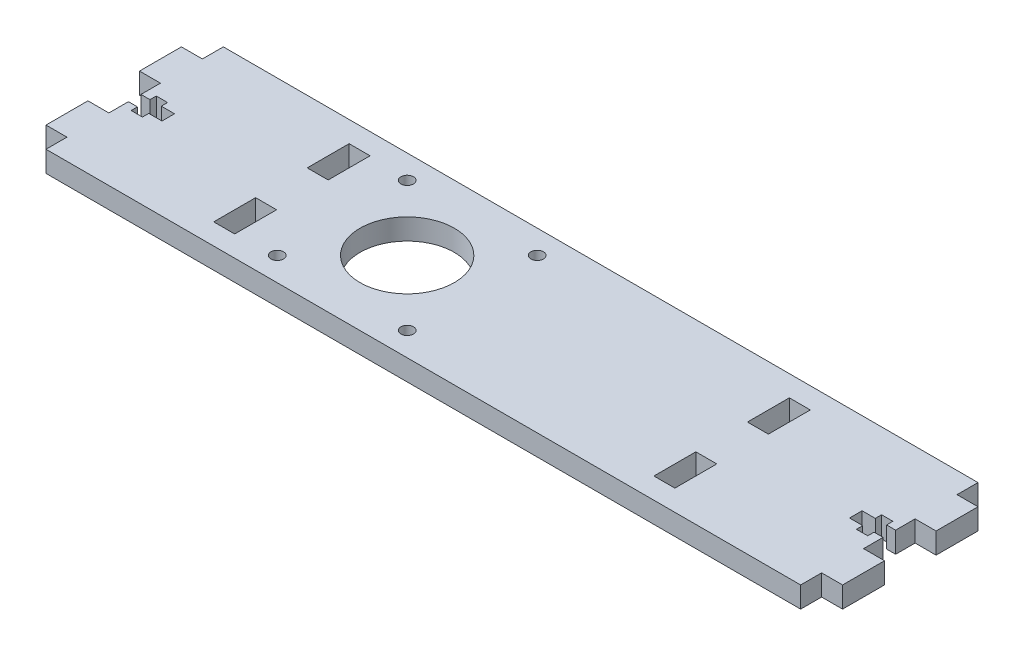
SolidWorks part; units mm, degrees
ref_plane "前视基准面" through (0, 0, 0) normal (0, 0, 1) x (1, 0, 0)
ref_plane "上视基准面" through (0, 0, 0) normal (0, 1, 0) x (1, 0, 0)
ref_plane "右视基准面" through (0, 0, 0) normal (1, 0, 0) x (0, 0, -1)
sketch "草图1" plane through (0, 0, 0) normal (0, 1, 0) x (1, 0, 0)
  line L0 (-5, 66.5434) -> (-5, -19.0663) construction
  line L1 (0, 0) -> (180, 0)
  line L2 (0, 0) -> (0, 5)
  line L3 (0, 42.3) -> (81, 42.3)
  line L4 (180, 0) -> (180, 5)
  line L5 (35, 79.204) -> (35, -20.674) construction
  line L6 (140, 82.0175) -> (140, -23.8894) construction
  line L7 (40, 79.204) -> (40, -15.449) construction
  line L8 (145, 75.274) -> (145, -20.674) construction
  line L9 (-24.6648, 21.15) -> (199.6086, 21.15) construction
  line L10 (90, 93.9854) -> (90, -20.674) construction
  line L11 (65, 59.3981) -> (65, -15.449) construction
  line L12 (0, 37.3) -> (0, 42.3)
  line L13 (0, 37.3) -> (-5, 37.3)
  line L14 (0, 15) -> (0, 19.659)
  line L15 (0, 27.3) -> (-5, 27.3)
  line L16 (-5, 37.3) -> (-5, 27.3)
  line L17 (0, 15) -> (-5, 15)
  line L18 (180, 37.3) -> (180, 42.3)
  line L19 (0, 5) -> (-5, 5)
  line L20 (-5, 15) -> (-5, 5)
  line L21 (180, 37.3) -> (185, 37.3)
  line L22 (180, 15) -> (180, 19.659)
  line L23 (180, 27.3) -> (185, 27.3)
  line L24 (185, 37.3) -> (185, 27.3)
  line L25 (180, 15) -> (185, 15)
  line L26 (99, 42.3) -> (180, 42.3)
  line L27 (180, 5) -> (185, 5)
  line L28 (185, 15) -> (185, 5)
  line L29 (49.5, 36.65) -> (80.5, 36.65) construction
  line L30 (49.5, 36.65) -> (49.5, 5.65) construction
  line L31 (49.5, 5.65) -> (80.5, 5.65) construction
  line L32 (80.5, 36.65) -> (80.5, 5.65) construction
  line L33 (49.5, 36.65) -> (80.5, 5.65) construction
  line L34 (49.5, 5.65) -> (80.5, 36.65) construction
  line L35 (35, 37.3) -> (40, 37.3)
  line L36 (35, 37.3) -> (35, 27.3)
  line L37 (35, 27.3) -> (40, 27.3)
  line L38 (40, 37.3) -> (40, 27.3)
  line L39 (35, 15) -> (40, 15)
  line L40 (35, 15) -> (35, 5)
  line L41 (35, 5) -> (40, 5)
  line L42 (40, 15) -> (40, 5)
  line L43 (140, 37.3) -> (145, 37.3)
  line L44 (140, 37.3) -> (140, 27.3)
  line L45 (140, 27.3) -> (145, 27.3)
  line L46 (145, 37.3) -> (145, 27.3)
  line L47 (140, 15) -> (145, 15)
  line L48 (140, 15) -> (140, 5)
  line L49 (140, 5) -> (145, 5)
  line L50 (145, 15) -> (145, 5)
  line L51 (81, 42.3) -> (99, 42.3)
  line L52 (0, 22.65) -> (2.15, 22.65)
  line L53 (8, 22.65) -> (8, 19.659)
  line L54 (8, 19.659) -> (4.85, 19.659)
  line L55 (2.15, 19.659) -> (2.15, 18.15)
  line L56 (2.15, 24.15) -> (4.85, 24.15)
  line L57 (2.15, 24.15) -> (2.15, 22.65)
  line L58 (2.15, 18.15) -> (4.85, 18.15)
  line L59 (4.85, 24.15) -> (4.85, 22.65)
  line L60 (2.15, 19.659) -> (0, 19.659)
  line L61 (4.85, 19.659) -> (4.85, 18.15)
  line L62 (4.85, 22.65) -> (8, 22.65)
  line L63 (180, 22.65) -> (177.85, 22.65)
  line L64 (177.85, 19.659) -> (180, 19.659)
  line L65 (177.85, 19.659) -> (177.85, 18.15)
  line L66 (175.15, 19.659) -> (175.15, 18.15)
  line L67 (177.85, 18.15) -> (175.15, 18.15)
  line L68 (172, 19.659) -> (175.15, 19.659)
  line L69 (172, 22.65) -> (172, 19.659)
  line L70 (175.15, 22.65) -> (172, 22.65)
  line L71 (175.15, 24.15) -> (175.15, 22.65)
  line L72 (177.85, 24.15) -> (177.85, 22.65)
  line L73 (177.85, 24.15) -> (175.15, 24.15)
  line L74 (0, 22.65) -> (0, 27.3)
  line L75 (180, 22.65) -> (180, 27.3)
  circle A0 centre (65, 21.15) radius 11.25
  circle A1 centre (49.5, 36.65) radius 1.5
  circle A2 centre (80.5, 36.65) radius 1.5
  circle A3 centre (80.5, 5.65) radius 1.5
  circle A4 centre (49.5, 5.65) radius 1.5
  point P66 (3.5591, 21.15)
  point P69 (94, 42.3)
  point P74 (94, 24.3)
  dimension "D21" = 5
  dimension "D32" = 2.7
  dimension "D33" = 1.509
  dimension "D2" = 42.3
  dimension "D3" = 5
  dimension "D4" = 5
  dimension "D5" = 5
  dimension "D6" = 21.15
  dimension "D7" = 90
  dimension "D8" = 50
  dimension "D9" = 50
  dimension "D10" = 25
  dimension "D11" = 10
  dimension "D12" = 10
  dimension "D13" = 5
  dimension "D14" = 5
  dimension "D15" = 5
  dimension "D16" = 5
  dimension "D17" = 10
  dimension "D18" = 10
  dimension "D19" = 5
  dimension "D20" = 5
  dimension "D22" = 5
  dimension "D23" = 10
  dimension "D24" = 10
  dimension "D25" = 5
  dimension "D26" = 5
  dimension "D27" = 10
  dimension "D28" = 10
  dimension "D29" = 18
  dimension "D30" = 2.7
  dimension "D31" = 1.5
  dimension "D34" = 3.15
  dimension "D35" = 2.15
  dimension "D36" = 6
  dimension "D37" = 2.15
extrude "凸台-拉伸1" add sketch "草图1" along normal blind 5
